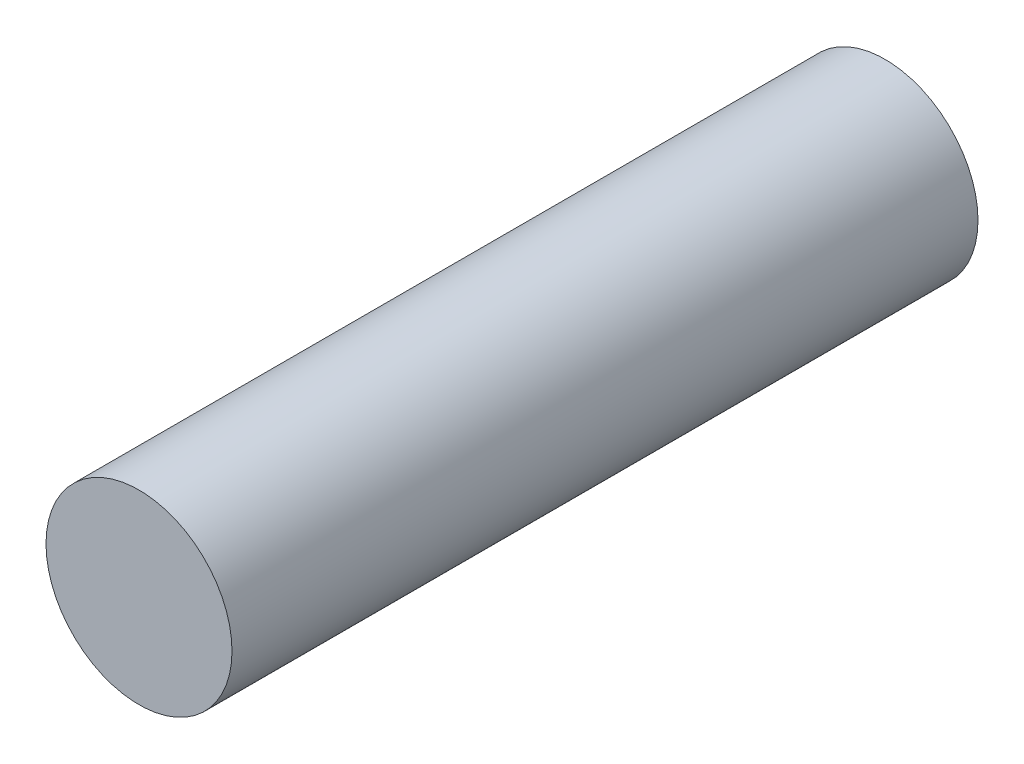
SolidWorks part; units mm, degrees
ref_plane "Front Plane" through (0, 0, 0) normal (0, 0, 1) x (1, 0, 0)
ref_plane "Top Plane" through (0, 0, 0) normal (0, 1, 0) x (1, 0, 0)
ref_plane "Right Plane" through (0, 0, 0) normal (1, 0, 0) x (0, 0, -1)
sketch "Sketch2" plane through (0, 0, 0) normal (0, 0, 1) x (1, 0, 0)
  circle A0 centre (0, 0) radius 0.0935
  dimension "D1" = 0.187
extrude "Boss-Extrude1" add sketch "Sketch2" along normal blind 0.75
